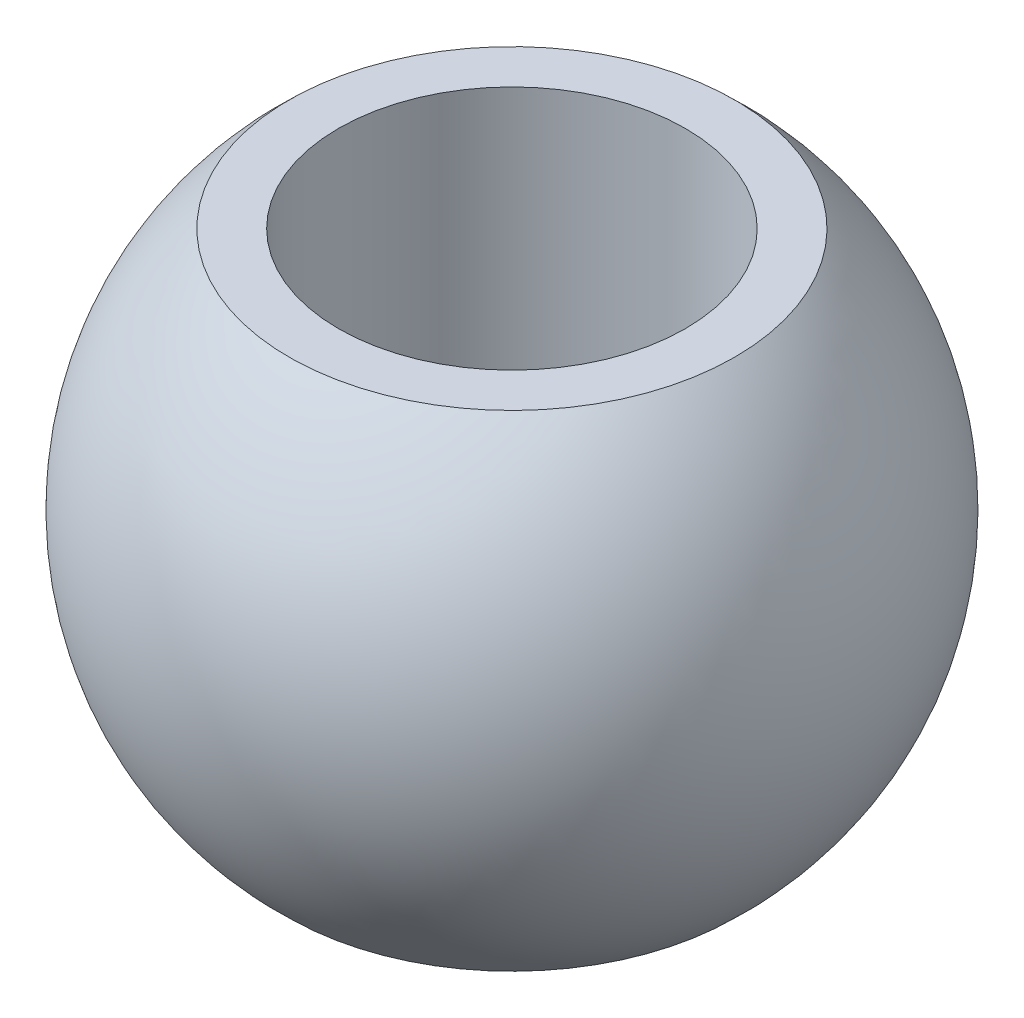
SolidWorks part; units mm, degrees
ref_plane "Ön Düzlem" through (0, 0, 0) normal (0, 0, 1) x (1, 0, 0)
ref_plane "Üst Düzlem" through (0, 0, 0) normal (0, 1, 0) x (1, 0, 0)
ref_plane "Sağ Düzlem" through (0, 0, 0) normal (1, 0, 0) x (0, 0, -1)
ref_plane "Plane1" through (0, 0, 0) normal (0, 0, -1) x (-1, 0, 0)
sketch "Sketch1" plane through (0, 0, 0) normal (0, 0, -1) x (-1, 0, 0)
  line L0 (-6.4226, -7) -> (-5, -7)
  line L1 (-5, -7) -> (-5, 7)
  line L2 (-5, 7) -> (-6.4226, 7)
  line L3 (0, -7) -> (0, 7) construction
  arc A0 (-6.4226, 7) -> (-6.4226, -7) centre (0, 0) ccw
revolve "Revolve1" add sketch "Sketch1" angle 360 about L3
